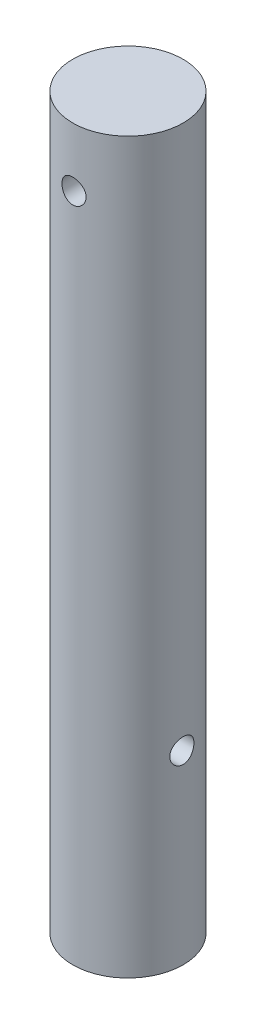
SolidWorks part; units mm, degrees
ref_plane "Front Plane" through (0, 0, 0) normal (0, 0, 1) x (1, 0, 0)
ref_plane "Top Plane" through (0, 0, 0) normal (0, 1, 0) x (1, 0, 0)
ref_plane "Right Plane" through (0, 0, 0) normal (1, 0, 0) x (0, 0, -1)
sketch "Sketch1" plane through (0, 0, 0) normal (0, 1, 0) x (1, 0, 0)
  circle A0 centre (0, 0) radius 4.7625
  dimension "D1" = 9.525
extrude "Boss-Extrude1" add sketch "Sketch1" against normal blind 9.525
sketch "Sketch2" plane through (0, -9.525, 0) normal (0, -1, 0) x (-1, 0, 0)
  circle A0 centre (0, 0) radius 4.7625
  dimension "D1" = 9.525
extrude "Boss-Extrude2" add sketch "Sketch2" along normal blind 53.34
sketch "Sketch3" plane through (0, 0, 0) normal (0, 0, 1) x (1, 0, 0)
  circle A0 centre (0, -5.08) radius 1.0414
  dimension "D1" = 2.0828
  dimension "D2" = 5.08
extrude "Cut-Extrude1" cut sketch "Sketch3" against normal up to surface and the other way up to surface up to face at (0, 0, 4.7625) other way up to face at (0, 0, 4.7625)
sketch "Sketch4" plane through (0, 0, 0) normal (1, 0, 0) x (0, 0, -1)
  line L0 (-4.7625, -62.865) -> (4.7625, -62.865) construction
  circle A0 centre (0, -46.863) radius 1.0414
  dimension "D1" = 2.0828
  dimension "D2" = 16.002
extrude "Cut-Extrude2" cut sketch "Sketch4" against normal up to surface and the other way up to surface up to face at (1.0196, -4.8679, 4.6521) other way up to face at (1.0196, -4.8679, 4.6521)
